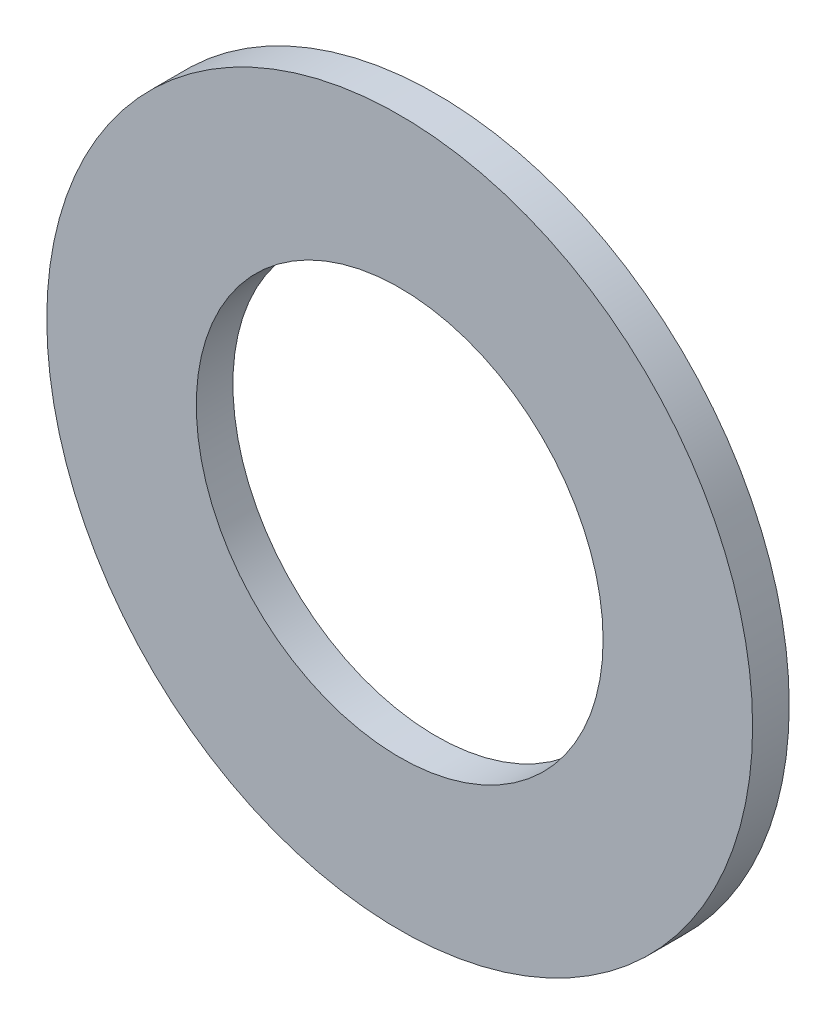
SolidWorks part; units mm, degrees
ref_plane "Plan1" through (0, 0, 0) normal (0, 0, 1) x (1, 0, 0)
ref_plane "Plan2" through (0, 0, 0) normal (0, 1, 0) x (1, 0, 0)
ref_plane "Plan3" through (0, 0, 0) normal (1, 0, 0) x (0, 0, -1)
sketch "Esquisse1" plane through (0, 0, 0) normal (0, 0, 1) x (1, 0, 0)
  circle A0 centre (0, 0) radius 17.35
  circle A1 centre (0, 0) radius 10
  dimension "D1" = 20
  dimension "D2" = 34.7
extrude "Base-Extrusion" add sketch "Esquisse1" along normal blind 1.8
